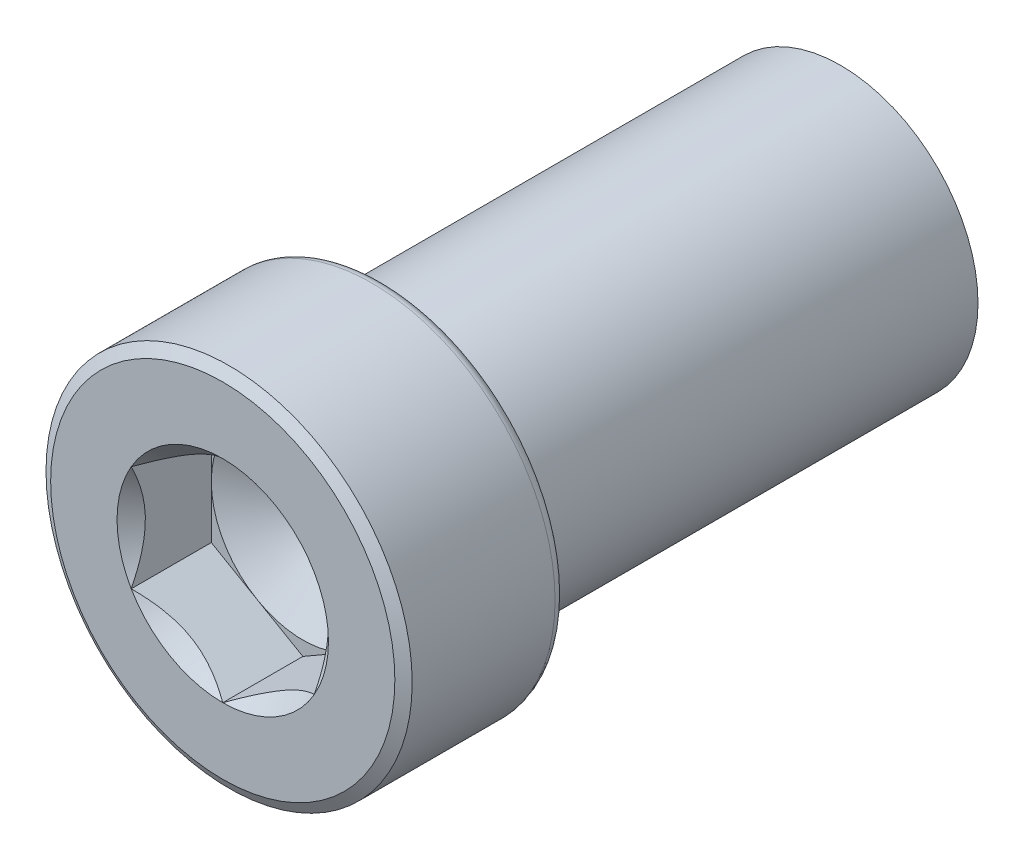
SolidWorks part; units mm, degrees
material "Chrome Stainless Steel"
ref_plane "Front" through (0, 0, 0) normal (0, 0, 1) x (1, 0, 0)
ref_plane "Top" through (0, 0, 0) normal (0, 1, 0) x (1, 0, 0)
ref_plane "Right" through (0, 0, 0) normal (1, 0, 0) x (0, 0, -1)
sketch "Sketch1" plane through (0, 0, 0) normal (1, 0, 0) x (0, 0, -1)
  line L0 (0, 0) -> (-2, 0) construction
  line L1 (0, 0) -> (20, 0)
  line L2 (0, 0) -> (0, 6)
  line L3 (0, 6) -> (20, 6)
  line L4 (20, 0) -> (20, 6)
  line L5 (0, -6) -> (20, -6) construction
  dimension "D1" = 2
  dimension "Thread Dia" = 12
  dimension "Screw Length" = 20
revolve "Revolve1" add sketch "Sketch1" angle 360 about L0
sketch "Sketch2" plane through (0, 0, 0) normal (1, 0, 0) x (0, 0, -1)
  line L0 (0, 6) -> (0, -6) construction
  line L1 (0, -6) -> (1.75, -6) construction
  line L2 (1.75, -6) -> (0, 6) construction
  line L3 (0, 6) -> (0.2165, 6.0316) construction
  line L4 (0.2165, 6.0316) -> (1.7317, 6.2525)
  line L5 (1.7317, 6.2525) -> (1.3272, 5.2363)
  line L6 (1.3272, 5.2363) -> (0.8943, 5.1732)
  line L7 (0.8943, 5.1732) -> (0.2165, 6.0316)
  line L8 (1.1108, 5.2048) -> (0.9741, 6.1421) construction
  line L9 (0, -6) -> (20, -6) construction
  line L10 (0, 6) -> (20, 6) construction
  line L12 (0.9948, 6) -> (2.7448, -6) construction
  line L13 (0, -0.2727) -> (3.7396, 0.2727) construction
  line L15 (0, 0) -> (0, 6) construction
  point P19 (1.8698, 0)
  dimension "D1" = 60
  dimension "Thread Pitch" = 1.75
  dimension "D2" = 0.2188
  dimension "D3" = 0.4375
  dimension "D4" = 1.75
revolve "Cut-Revolve1" [suppressed] cut sketch "Sketch2" angle 360 about L13
sketch "Sketch3" plane through (0, 0, 0) normal (1, 0, 0) x (0, 0, -1)
  line L0 (20, 5.1732) -> (17.7283, 6)
  line L1 (17.7283, 6) -> (20, 6)
  line L2 (20, 6) -> (20, 5.1732)
  line L3 (0, 6) -> (20, 6) construction
  line L4 (20, 0) -> (20, 6) construction
  line L5 (17.7283, 0) -> (0, 0) construction
  line L6 (17.7283, 6) -> (17.7283, -6) construction
  line L7 (0, -6) -> (20, -6) construction
  dimension "D1" = 20
  dimension "D2" = 12
revolve "Cut-Revolve2" [suppressed] cut sketch "Sketch3" angle 360 about L5
pattern_linear "LPattern1" [suppressed] count 11 spacing 1.75 along (0, 0, 1)
pattern_linear "LPattern3" [suppressed] count 2 spacing 1.75 along (0, 0, 1)
sketch "Sketch4" plane through (0, 0, 0) normal (0, 0, 1) x (1, 0, 0)
  circle A0 centre (0, 0) radius 8
  dimension "Head Dia" = 16
extrude "Extrude1" add sketch "Sketch4" along normal blind 7
fillet "Fillet1" radius 0.48 1 edges at (8, 0, 0)
chamfer "Chamfer1" distance 0.48 angle 30 1 edges at (8, 0, 7)
sketch "Sketch6" plane through (0, 0, 7) normal (0, 0, 1) x (1, 0, 0)
  line L1 (0, -4.6188) -> (4, -2.3094)
  line L2 (4, -2.3094) -> (4, 2.3094)
  line L3 (4, 2.3094) -> (0, 4.6188)
  line L4 (0, 4.6188) -> (-4, 2.3094)
  line L5 (-4, 2.3094) -> (-4, -2.3094)
  line L6 (-4, -2.3094) -> (0, -4.6188)
  circle A0 centre (0, 0) radius 4 construction
  dimension "Hex" = 8
extrude "Cut-Extrude1" cut sketch "Sketch6" against normal blind 3.5
sketch "Sketch7" plane through (0, 0, 7) normal (0, 0, 1) x (1, 0, 0)
  circle A0 centre (0, 0) radius 4.6188
extrude "Cut-Extrude4" cut sketch "Sketch7" against normal blind 3.5 draft 45
sketch "Sketch8" plane through (0, 0, 3.5) normal (0, 0, 1) x (1, 0, 0)
  circle A0 centre (0, 0) radius 4 construction
  circle A1 centre (0, 0) radius 4
extrude "Cut-Extrude5" cut sketch "Sketch8" against normal blind 1.1667 draft 60
equation "\"D1@Sketch1\"=\"Screw Length@Sketch1\"/10"
equation "\"D2@Sketch2\"=\"Thread Pitch@Sketch2\"/8"
equation "\"D3@Sketch2\"=\"Thread Pitch@Sketch2\"/4"
equation "\"D4@Sketch2\"=\"Thread Pitch@Sketch2\""
equation "\"D3@LPattern1\"=\"Thread Pitch@Sketch2\""
equation "\"D1@Fillet1\"=\"Thread Dia@Sketch1\"/25"
equation "\"D1@Chamfer1\"=\"D1@Fillet1\""
equation "\"D1@Cut-Extrude1\"=\"Head Height@Extrude1\"/2"
equation "\"D1@Cut-Extrude4\"=\"D1@Cut-Extrude1\""
equation "\"D1@Cut-Extrude5\"=\"D1@Cut-Extrude1\"/3"
equation "\"D1@LPattern1\"=\"Screw Length@Sketch1\"/\"Thread Pitch@Sketch2\""
equation "\"D3@LPattern3\"=\"Thread Pitch@Sketch2\""
